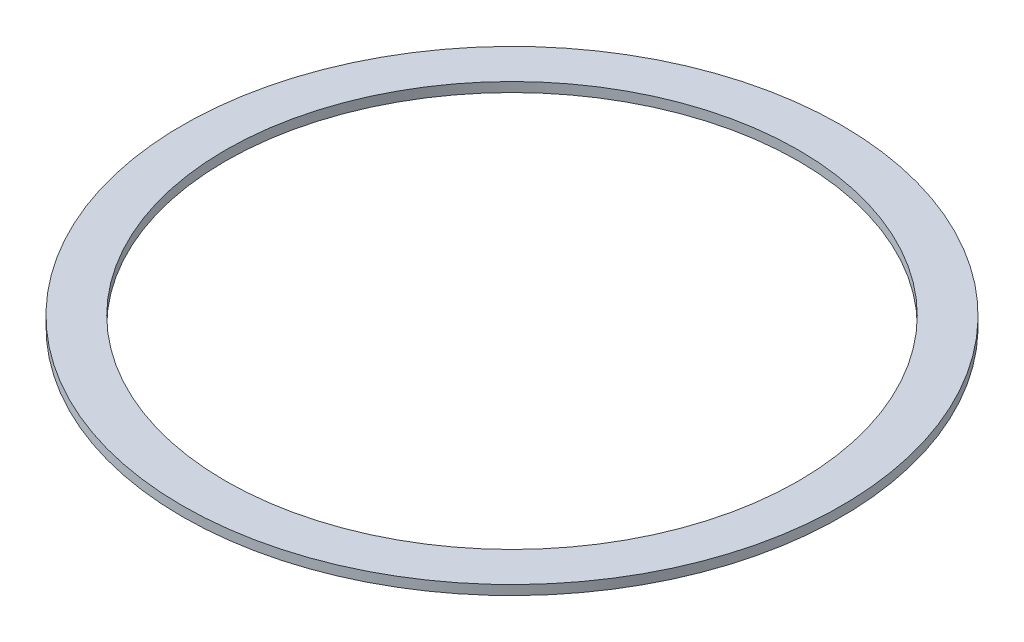
SolidWorks part; units mm, degrees
ref_plane "Front Plane" through (0, 0, 0) normal (0, 0, 1) x (1, 0, 0)
ref_plane "Top Plane" through (0, 0, 0) normal (0, 1, 0) x (1, 0, 0)
ref_plane "Right Plane" through (0, 0, 0) normal (1, 0, 0) x (0, 0, -1)
sketch "Sketch1" plane through (0, 0, 0) normal (0, 1, 0) x (1, 0, 0)
  circle A0 centre (0, 0) radius 60
  circle A1 centre (0, 0) radius 69
  dimension "D1" = 120
  dimension "D2" = 138
extrude "Boss-Extrude1" add sketch "Sketch1" along normal blind 2
